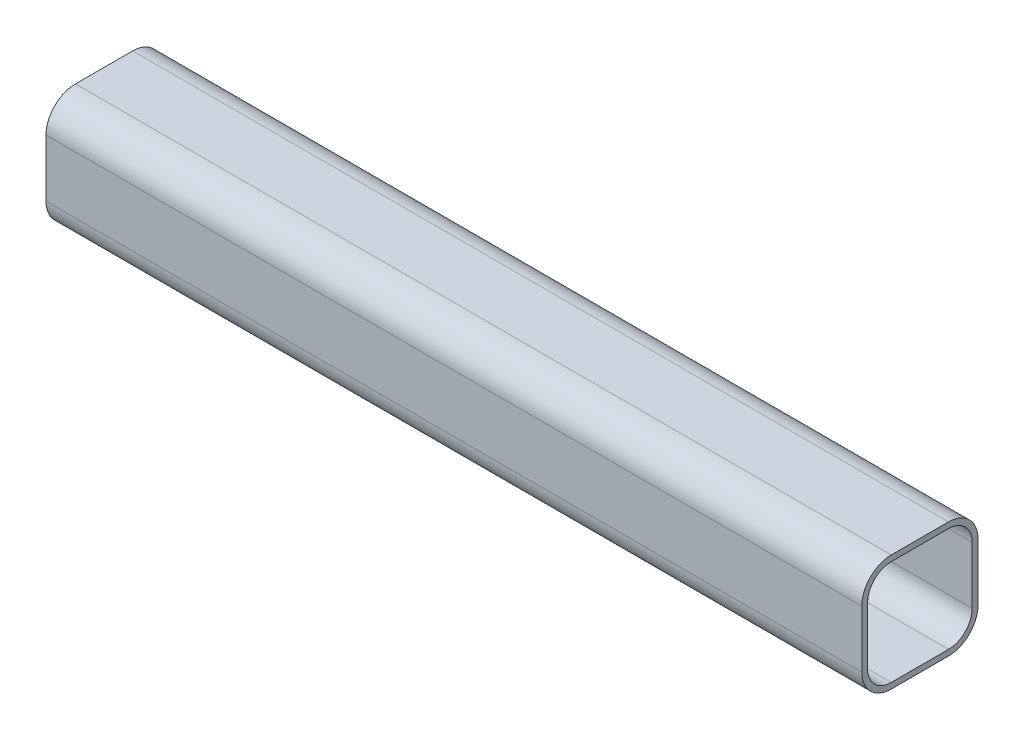
SolidWorks part; units mm, degrees
material "AISI 1015 Acero estirado en frío (SS)"
ref_plane "Alzado" through (0, 0, 0) normal (0, 0, 1) x (1, 0, 0)
ref_plane "Planta" through (0, 0, 0) normal (0, 1, 0) x (1, 0, 0)
ref_plane "Vista lateral" through (0, 0, 0) normal (1, 0, 0) x (0, 0, -1)
sketch "Croquis1" plane through (0, 0, 0) normal (0, 0, 1) x (1, 0, 0)
  line L0 (-136.2138, 0) -> (214.7862, 0)
  dimension "D1" = 351
other "Miembro estructural1"
ref_plane "Plano1" through (-136.2138, 0, 0) normal (1, 0, 0) x (0, 1, 0)
sketch "Sketch11" plane through (-136.2138, 0, 0) normal (1, 0, 0) x (0, 1, 0)
  line L0 (-12.3, -22.5) -> (12.3, -22.5)
  line L1 (-22.5, -12.3) -> (-22.5, 12.3)
  line L2 (12.3, 22.5) -> (-12.3, 22.5)
  line L3 (22.5, 12.3) -> (22.5, -12.3)
  line L4 (-12.3, -25) -> (12.3, -25)
  line L5 (-25, -12.3) -> (-25, 12.3)
  line L6 (12.3, 25) -> (-12.3, 25)
  line L7 (25, 12.3) -> (25, -12.3)
  line L8 (0, 0) -> (22.5, 0) construction
  line L9 (0, 0) -> (0, 22.5) construction
  arc A0 (25, 12.3) -> (12.3, 25) centre (12.3, 12.3) ccw
  arc A1 (12.3, -25) -> (25, -12.3) centre (12.3, -12.3) ccw
  arc A2 (-25, -12.3) -> (-12.3, -25) centre (-12.3, -12.3) ccw
  arc A3 (-12.3, 25) -> (-25, 12.3) centre (-12.3, 12.3) ccw
  arc A4 (-12.3, 22.5) -> (-22.5, 12.3) centre (-12.3, 12.3) ccw
  arc A5 (22.5, 12.3) -> (12.3, 22.5) centre (12.3, 12.3) ccw
  arc A6 (12.3, -22.5) -> (22.5, -12.3) centre (12.3, -12.3) ccw
  arc A7 (-22.5, -12.3) -> (-12.3, -22.5) centre (-12.3, -12.3) ccw
  point P3 (0, 25)
  point P4 (25, 0)
  point P5 (0, -25)
  point P6 (-25, 0)
  point P7 (-25, 25)
  point P8 (-25, -25)
  point P33 (0, 0)
  point P35 (25, -25)
  point P36 (25, 25)
  point P37 (0, 0)
  dimension "D1" = 12.7
  dimension "Thickness" = 2.5
  dimension "V_leg" = 50
